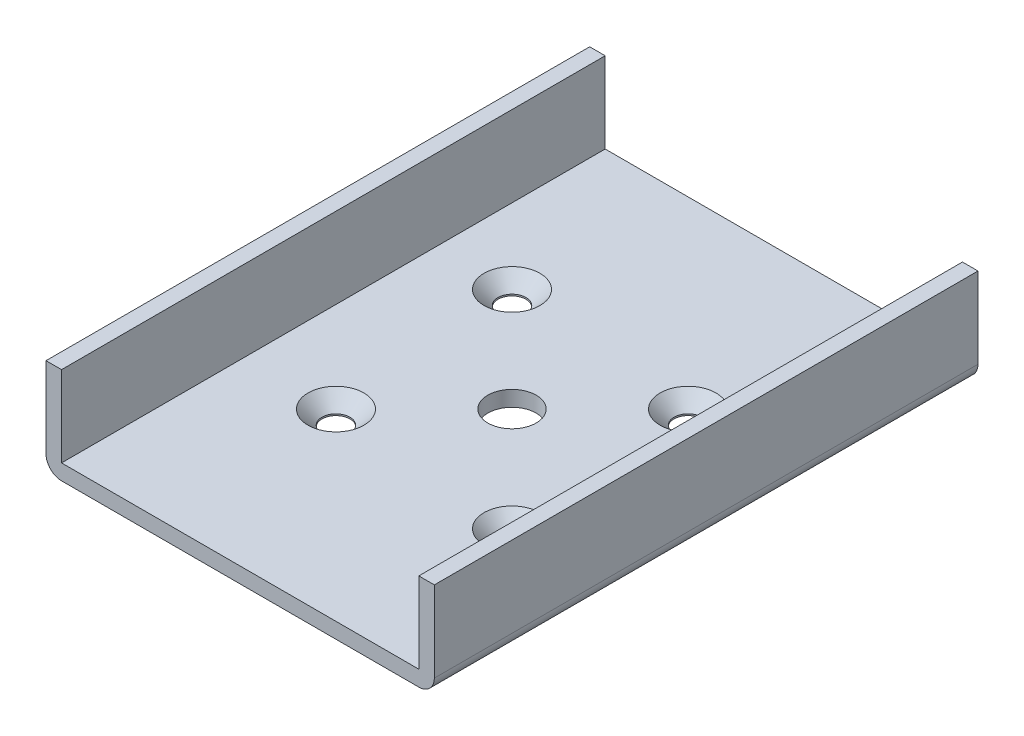
SolidWorks part; units mm, degrees
ref_plane "Front Plane" through (0, 0, 0) normal (0, 0, 1) x (1, 0, 0)
ref_plane "Top Plane" through (0, 0, 0) normal (0, 1, 0) x (1, 0, 0)
ref_plane "Right Plane" through (0, 0, 0) normal (1, 0, 0) x (0, 0, -1)
sketch "Sketch1" plane through (0, 0, 0) normal (0, 0, 1) x (1, 0, 0)
  line L0 (-12.5, 6.2) -> (-12.5, 1)
  line L1 (-11.5, 0) -> (11.5, 0)
  line L2 (12.5, 1) -> (12.5, 6.2)
  arc A0 (11.5, 0) -> (12.5, 1) centre (11.5, 1) ccw
  arc A1 (-12.5, 1) -> (-11.5, 0) centre (-11.5, 1) ccw
  point P5 (0, 0)
  point P8 (12.5, 0)
  point P11 (-12.5, 0)
  dimension "D3" = 1
  dimension "D1" = 25
  dimension "D2" = 6.2
extrude "Extrude-Thin1" add sketch "Sketch1" along normal blind 35 thin
sketch "Sketch2" plane through (0, 1, 0) normal (0, 1, 0) x (1, 0, 0)
  circle A0 centre (0, -17.5) radius 1.5558 construction
  circle A1 centre (0, -17.5) radius 1.5558
extrude "Cut-Extrude1" cut sketch "Sketch2" against normal up to surface (2.4732 mm away)
sketch "Sketch3" plane through (0, 1, 0) normal (0, 1, 0) x (1, 0, 0)
  point P0 (-6.6723, -10.8277)
  point P1 (-5.6665, -23.1665)
  point P3 (6.6723, -24.1723)
  point P5 (5.6665, -11.8335)
hole_wizard "CSK for M1.6 Countersunk Flat Head Screw1" positions "3DSketch1" profile "Sketch4" countersink size "M1.6" standard "ISO"
sketch3d "3DSketch1"
  point P0 (5.6665, 1, 11.8335)
  point P3 (6.6723, 1, 24.1723)
  point P6 (-5.6665, 1, 23.1665)
  point P9 (-6.6723, 1, 10.8277)
sketch "Sketch4" plane through (5.6665, 1, 11.8335) normal (1, 0, 0) x (0, 0, 1)
  line L0 (0, 0) -> (0, 119.5408)
  line L1 (0, 119.5408) -> (0.9, 119)
  line L2 (0.9, 119) -> (0.9, 0.9)
  line L3 (0.9, 0.9) -> (1.8, 0)
  line L5 (1.8, 0) -> (0, 0)
  line L6 (-0.9, 0.9) -> (-1.8, 0) construction
  line L10 (0, 119.5408) -> (-0.9, 119) construction
  line L11 (0, -6.35) -> (0, 107.95) construction
  dimension "Hole Dia." = 1.8
  dimension "Hole Depth" = 119
  dimension "Near C'Sink Dia." = 3.6
  dimension "Near C'Sink Angle" = 90
  dimension "Drill Angle" = 118
